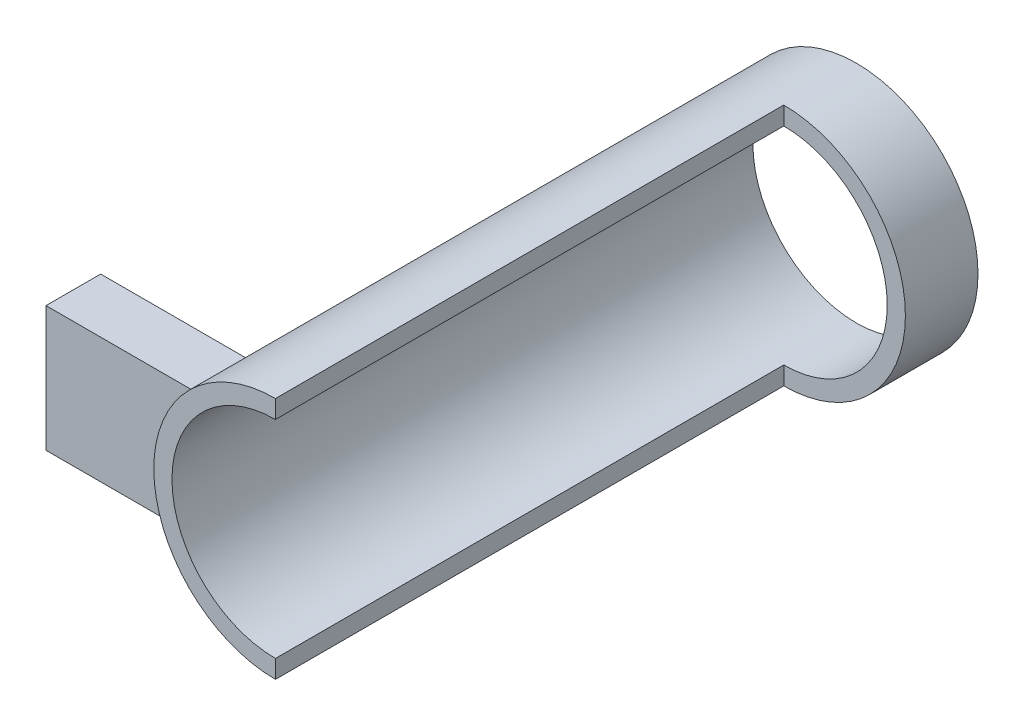
SolidWorks part; units mm, degrees
ref_plane "Plan de face" through (0, 0, 0) normal (0, 0, 1) x (1, 0, 0)
ref_plane "Plan de dessus" through (0, 0, 0) normal (0, 1, 0) x (1, 0, 0)
ref_plane "Plan de droite" through (0, 0, 0) normal (1, 0, 0) x (0, 0, -1)
sketch "Esquisse1" plane through (0, 0, 0) normal (0, 0, 1) x (1, 0, 0)
  circle A0 centre (0, 0) radius 2.85
  circle A1 centre (0, 0) radius 3.35
extrude "Boss.-Extru.1" add sketch "Esquisse1" along normal blind 2
sketch "Esquisse2" plane through (0, 0, 2) normal (0, 0, 1) x (1, 0, 0)
  line L0 (0, 3.35) -> (0, 2.85)
  line L1 (0, -2.85) -> (0, -3.35)
  circle A0 centre (0, 0) radius 2.85 construction
  circle A1 centre (0, 0) radius 3.35
  arc A2 (0, 3.35) -> (0, -3.35) centre (0, 0) ccw
  arc A3 (0, 2.85) -> (0, -2.85) centre (0, 0) ccw
  dimension "D1" = 0
extrude "Boss.-Extru.2" add sketch "Esquisse2" along normal blind 14
sketch "Esquisse3" plane through (0, 0, 0) normal (1, 0, 0) x (0, 0, -1)
  line L5 (-15.3194, 1.726) -> (-13.814, 1.726)
  line L6 (-15.3194, 1.726) -> (-15.3194, -1.726)
  line L7 (-15.3194, -1.726) -> (-13.814, -1.726)
  line L8 (-13.814, 1.726) -> (-13.814, -1.726)
  line L9 (-15.3194, 1.726) -> (-13.814, -1.726) construction
  line L10 (-15.3194, -1.726) -> (-13.814, 1.726) construction
  point P0 (-14.5667, 0)
extrude "Boss.-Extru.3" add sketch "Esquisse3" against normal blind 7
sketch "Esquisse4" plane through (0, 0, 16) normal (0, 0, 1) x (1, 0, 0)
  circle A1 centre (0, 0) radius 2.85
extrude "Enlèv. mat.-Extru.1" cut sketch "Esquisse4" against normal blind 5
